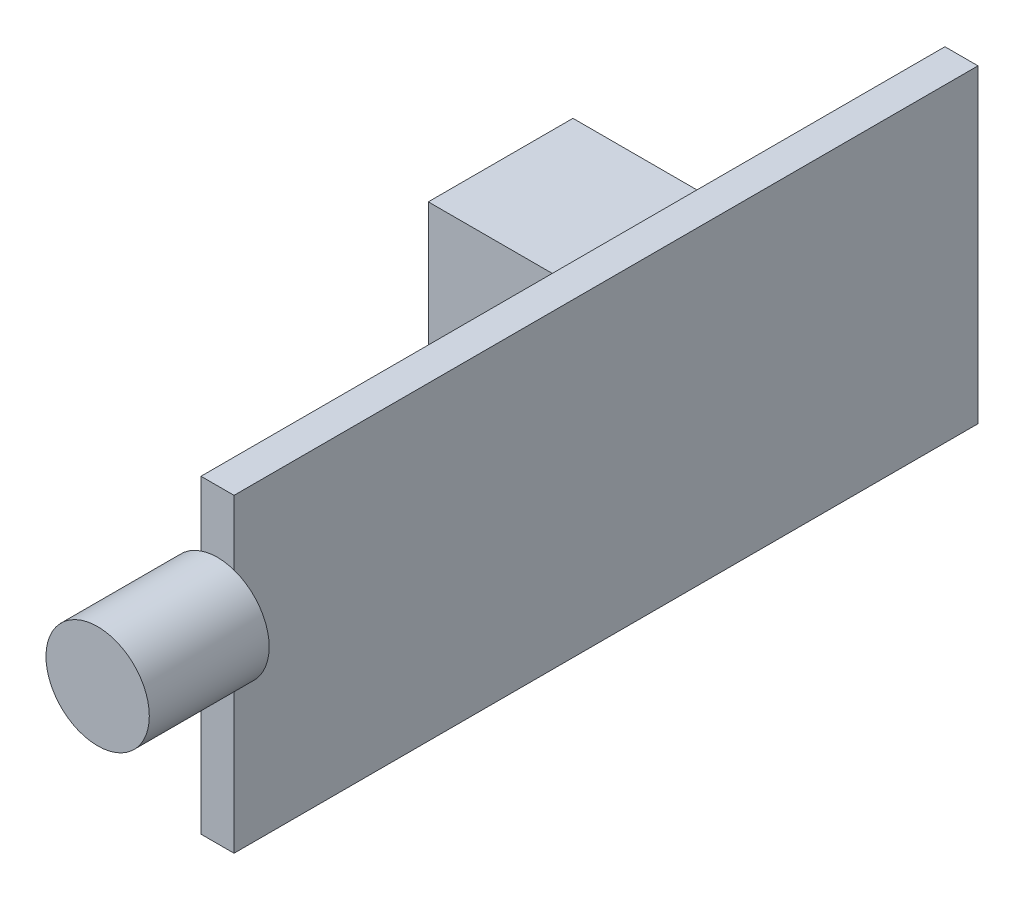
SolidWorks part; units mm, degrees
ref_plane "Front Plane" through (0, 0, 0) normal (0, 0, 1) x (1, 0, 0)
ref_plane "Top Plane" through (0, 0, 0) normal (0, 1, 0) x (1, 0, 0)
ref_plane "Right Plane" through (0, 0, 0) normal (1, 0, 0) x (0, 0, -1)
ref_plane "Plane1" through (0, 0, 7) normal (0, 0, 1) x (1, 0, 0)
sketch "Sketch1" plane through (0, 0, 7) normal (0, 0, 1) x (1, 0, 0)
  line L1 (14.2, -128.5) -> (15.8, -128.5)
  line L2 (14.2, -128.5) -> (14.2, -113.5)
  line L3 (14.2, -113.5) -> (15.8, -113.5)
  line L4 (15.8, -128.5) -> (15.8, -113.5)
  line L5 (14.2, -128.5) -> (15.8, -113.5) construction
  line L6 (14.2, -113.5) -> (15.8, -128.5) construction
  point P0 (15, -121)
extrude "Boss-Extrude1" add sketch "Sketch1" along normal blind 36
ref_plane "Plane2" through (0, 0, 43) normal (0, 0, 1) x (1, 0, 0)
sketch "Sketch2" plane through (0, 0, 43) normal (0, 0, 1) x (1, 0, 0)
  circle A0 centre (15, -119) radius 2.5
extrude "Boss-Extrude2" add sketch "Sketch2" along normal blind 5.8
ref_plane "Plane3" through (0, 0, 18) normal (0, 0, 1) x (1, 0, 0)
sketch "Sketch3" plane through (0, 0, 18) normal (0, 0, 1) x (1, 0, 0)
  line L0 (14.2, -113.5) -> (14.2, -116.6315) construction
  line L1 (7.2, -120.5) -> (14.2, -120.5)
  line L2 (7.2, -120.5) -> (7.2, -114.5)
  line L3 (7.2, -114.5) -> (14.2, -114.5)
  line L4 (14.2, -120.5) -> (14.2, -114.5)
  line L5 (7.2, -120.5) -> (14.2, -114.5) construction
  line L6 (7.2, -114.5) -> (14.2, -120.5) construction
  point P0 (10.7, -117.5)
extrude "Boss-Extrude3" add sketch "Sketch3" along normal blind 7
